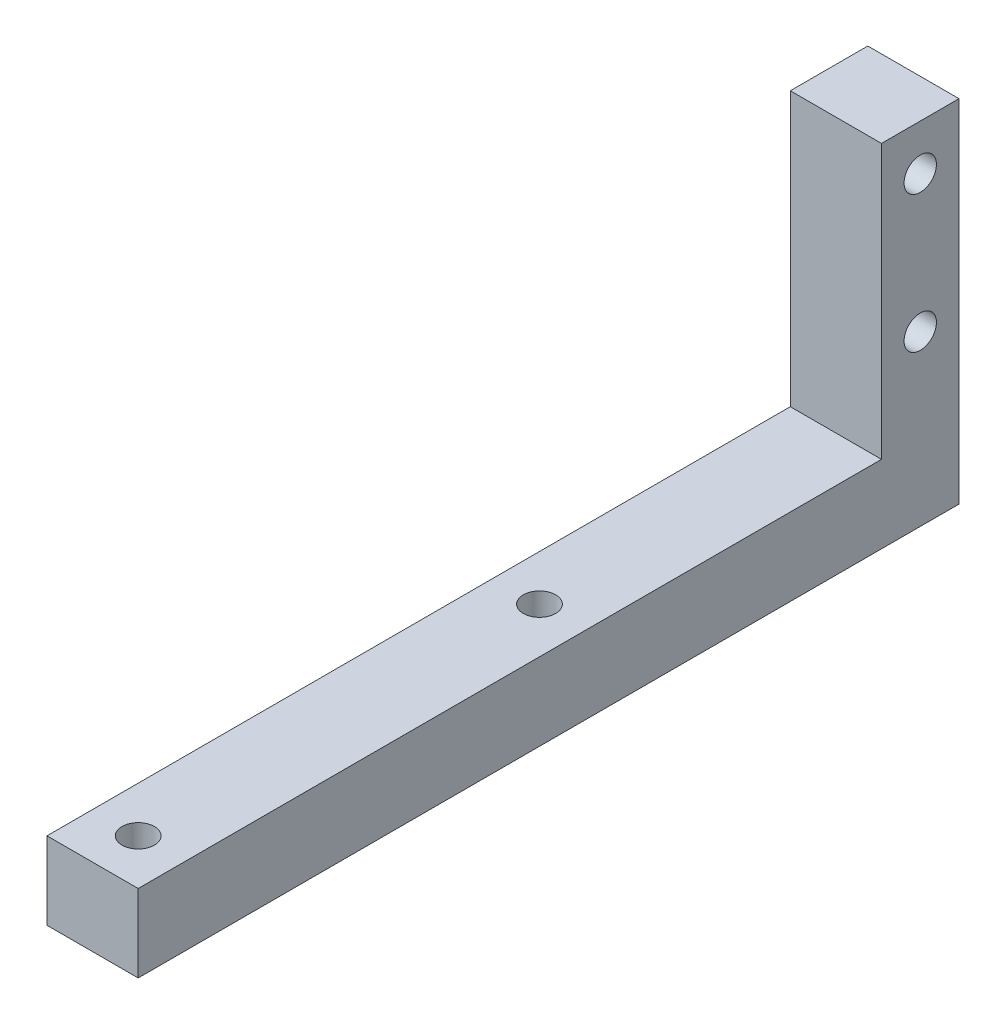
SolidWorks part; units mm, degrees
ref_plane "Front Plane" through (0, 0, 0) normal (0, 0, 1) x (1, 0, 0)
ref_plane "Top Plane" through (0, 0, 0) normal (0, 1, 0) x (1, 0, 0)
ref_plane "Right Plane" through (0, 0, 0) normal (1, 0, 0) x (0, 0, -1)
sketch "Sketch1" plane through (0, 0, 0) normal (1, 0, 0) x (0, 0, -1)
  line L0 (-56.0931, 4.6353) -> (25.4069, 4.6353)
  line L1 (25.4069, 4.6353) -> (25.4069, 34.6353)
  line L2 (25.4069, 34.6353) -> (33.9069, 34.6353)
  line L3 (33.9069, 34.6353) -> (33.9069, -3.8647)
  line L4 (33.9069, -3.8647) -> (-56.0931, -3.8647)
  line L5 (-56.0931, -3.8647) -> (-56.0931, 4.6353)
  line L6 (29.6569, -3.8647) -> (29.6569, 14.6353) construction
  line L7 (29.6569, 14.6353) -> (29.6569, 29.6353) construction
  line L8 (29.6569, 29.6353) -> (29.6569, 34.6353) construction
  circle A0 centre (29.6569, 14.6353) radius 1.775
  circle A1 centre (29.6569, 29.6353) radius 1.775
  dimension "D4" = 3.55
  dimension "D1" = 8.5
  dimension "D2" = 90
  dimension "D3" = 30
  dimension "D5" = 15
  dimension "D6" = 5
extrude "Boss-Extrude1" add sketch "Sketch1" along normal blind 10
sketch "Sketch2" plane through (0, 4.6353, 0) normal (0, 1, 0) x (1, 0, 0)
  line L0 (5, -56.0931) -> (5, 14.348) construction
  line L1 (10, -56.0931) -> (0, -56.0931) construction
  circle A0 centre (5, -51.0931) radius 1.775
  circle A1 centre (5, -7.0931) radius 1.775
  dimension "D1" = 3.55
  dimension "D2" = 44
  dimension "D3" = 5
extrude "Cut-Extrude1" cut sketch "Sketch2" against normal through all
